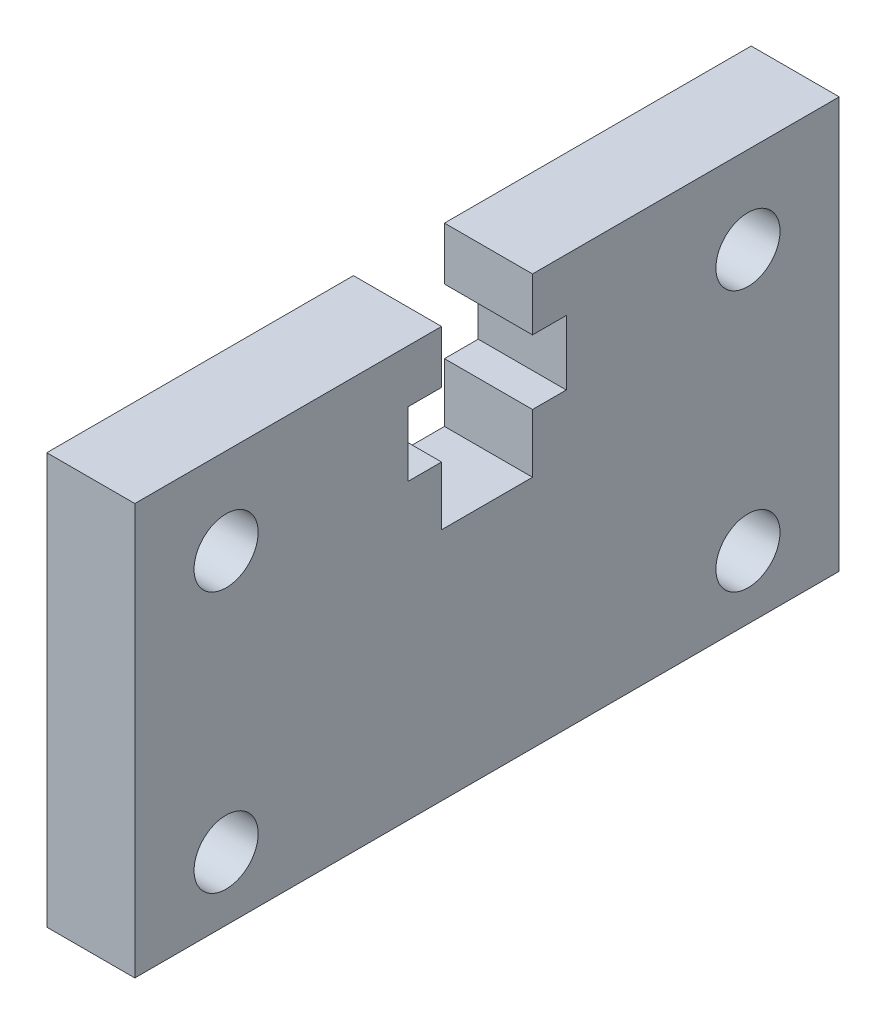
SolidWorks part; units mm, degrees
ref_plane "Front Plane" through (0, 0, 0) normal (0, 0, 1) x (1, 0, 0)
ref_plane "Top Plane" through (0, 0, 0) normal (0, 1, 0) x (1, 0, 0)
ref_plane "Right Plane" through (0, 0, 0) normal (1, 0, 0) x (0, 0, -1)
sketch "Sketch1" plane through (0, 0, 0) normal (1, 0, 0) x (0, 0, -1)
  line L1 (0, 0) -> (24, 0)
  line L2 (0, 0) -> (0, 14)
  line L3 (0, 14) -> (24, 14)
  line L4 (24, 0) -> (24, 14)
  dimension "D1" = 24
  dimension "D2" = 14
extrude "Boss-Extrude1" add sketch "Sketch1" along normal blind 3
hole_wizard "#44 (0.086) Diameter Hole3" positions "Sketch4" profile "Sketch5" hole size "#44" standard "ANSI Inch" end condition through all
sketch "Sketch4" plane through (3, 0, 0) normal (1, 0, 0) x (0, 0, -1)
  line L1 (24, 14) -> (0, 14) construction
  line L2 (0, 0) -> (24, 0) construction
  line L5 (0, 14) -> (0, 0) construction
  point P0 (3.11, 11.05)
  point P2 (20.89, 11.049)
  point P4 (20.89, 2.159)
  point P6 (3.11, 2.16)
  dimension "D1" = 17.78
  dimension "D2" = 17.78
  dimension "D3" = 8.89
  dimension "D6" = 2.159
  dimension "D4" = 3.11
  dimension "D10" = 2.951
  dimension "D8" = 3.11
  dimension "D5" = 2.16
sketch "Sketch5" plane through (3, 11.05, -3.11) normal (0, 1, 0) x (0, 0, -1)
  line L0 (0, 0) -> (0, 3)
  line L1 (0, 3) -> (1.0922, 3)
  line L2 (1.0922, 3) -> (1.0922, 0)
  line L5 (1.0922, 0) -> (0, 0)
  line L11 (0, -6.35) -> (0, 107.95) construction
  dimension "Thru Hole Dia." = 2.1844
  dimension "Thru Hole Depth" = 3
sketch "Sketch6" plane through (3, 0, 0) normal (1, 0, 0) x (0, 0, -1)
  line L0 (24, 14) -> (0, 14) construction
  line L1 (10.45, 14) -> (13.55, 14)
  line L2 (10.45, 14) -> (10.45, 8)
  line L3 (10.45, 8) -> (13.55, 8)
  line L4 (13.55, 14) -> (13.55, 8)
  line L5 (0, 14) -> (0, 0) construction
  line L12 (14.7, 12.2) -> (9.3, 12.2)
  line L13 (14.7, 12.2) -> (14.7, 10)
  line L14 (14.7, 10) -> (9.3, 10)
  line L15 (9.3, 12.2) -> (9.3, 10)
  dimension "D1" = 3.1
  dimension "D2" = 6
  dimension "D3" = 10.45
  dimension "D7" = 5.4
  dimension "D8" = 2.2
  dimension "D9" = 2
  dimension "D10" = 1.15
extrude "Cut-Extrude1" cut sketch "Sketch6" against normal blind 3
equation "\"D10@Sketch6\"=(5.4-3.1)/2"
equation "\"D4@Sketch4\"=(24-17.78)/2"
equation "\"D3@Sketch6\"=(24-3.1)/2"
